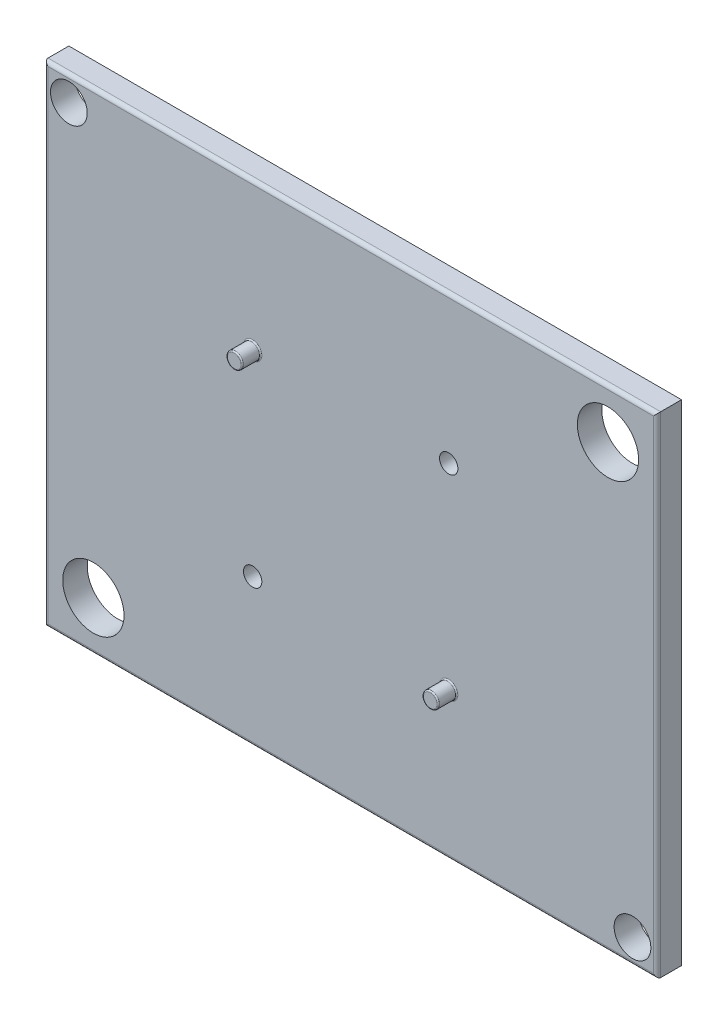
SolidWorks part; units mm, degrees
ref_plane "Ebene vorne" through (0, 0, 0) normal (0, 0, 1) x (1, 0, 0)
ref_plane "Ebene oben" through (0, 0, 0) normal (0, 1, 0) x (1, 0, 0)
ref_plane "Ebene rechts" through (0, 0, 0) normal (1, 0, 0) x (0, 0, -1)
sketch "Sketch1" plane through (0, 0, 0) normal (0, 0, 1) x (1, 0, 0)
  line L1 (-25, 20) -> (25, 20)
  line L2 (-25, 20) -> (-25, -20)
  line L3 (-25, -20) -> (25, -20)
  line L4 (25, 20) -> (25, -20)
  line L5 (-25, 20) -> (25, -20) construction
  line L6 (-25, -20) -> (25, 20) construction
  circle A0 centre (-23, 18) radius 1.5
  circle A1 centre (23, -18) radius 1.5
  circle A2 centre (8, 8) radius 0.75
  circle A3 centre (-8, -8) radius 0.75
  circle A4 centre (-21, -16) radius 2.5
  circle A5 centre (21, 16) radius 2.5
  point P0 (0, 0)
  dimension "D5" = 3
  dimension "D6" = 3
  dimension "D9" = 1.5
  dimension "D10" = 1.5
  dimension "D15" = 5
  dimension "D16" = 5
  dimension "D1" = 50
  dimension "D2" = 40
  dimension "D3" = 18
  dimension "D4" = 23
  dimension "D7" = 18
  dimension "D8" = 23
  dimension "D11" = 8
  dimension "D12" = 8
  dimension "D13" = 16
  dimension "D14" = 8
  dimension "D17" = 16
  dimension "D18" = 21
  dimension "D19" = 21
  dimension "D20" = 16
extrude "Boss-Extrude1" add sketch "Sketch1" along normal blind 2
fillet "Fillet1" radius 0.3 4 edges at (0, -20, 2) (25, 0, 2) (0, 20, 2) (-25, 0, 2)
sketch "Sketch2" plane through (0, 0, 0) normal (0, 0, 1) x (1, 0, 0)
  circle A0 centre (-8, 8) radius 0.65
  circle A1 centre (8, -8) radius 0.65
  dimension "D1" = 1.3
  dimension "D2" = 1.3
  dimension "D3" = 8
  dimension "D4" = 8
  dimension "D5" = 8
  dimension "D6" = 8
extrude "Boss-Extrude2" add sketch "Sketch2" along normal blind 2.5 from offset 1
fillet "Fillet2" radius 0.1 4 edges at (-7.35, 8, 2) (-7.35, 8, 3.5) (8.65, -8, 2) (8.65, -8, 3.5)
